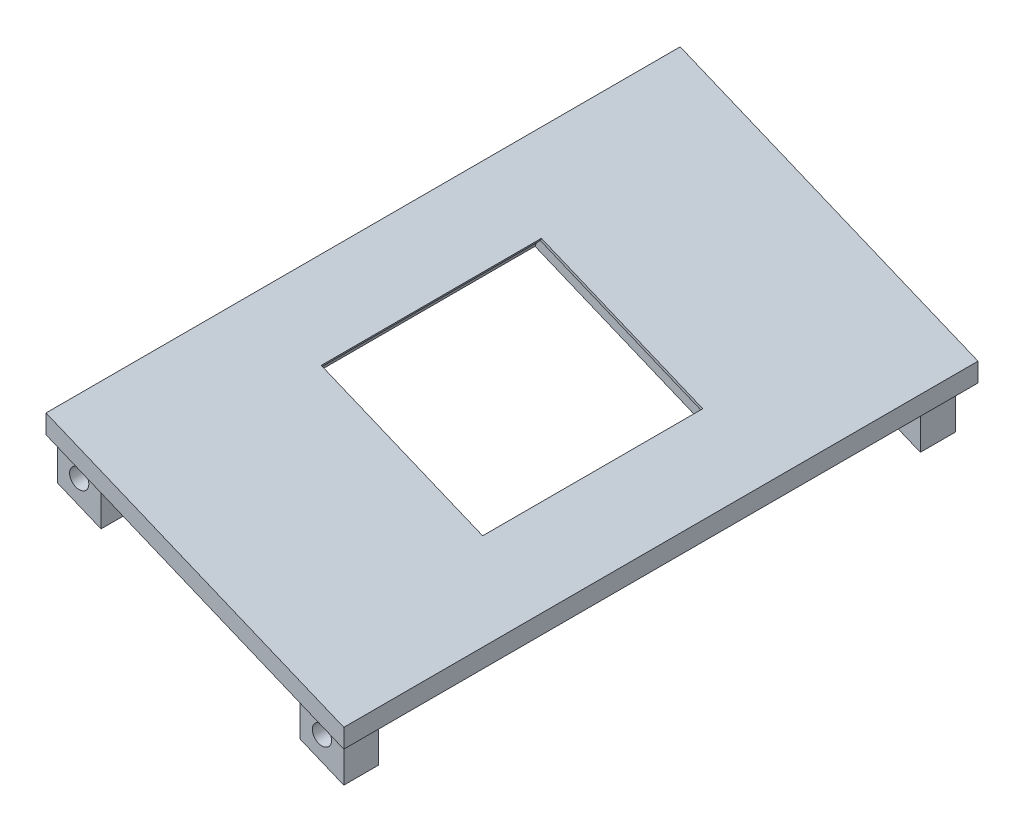
SolidWorks part; units mm, degrees
ref_plane "Ebene vorne" through (0, 0, 0) normal (0, 0, 1) x (1, 0, 0)
ref_plane "Ebene oben" through (0, 0, 0) normal (0, 1, 0) x (1, 0, 0)
ref_plane "Ebene rechts" through (0, 0, 0) normal (1, 0, 0) x (0, 0, -1)
sketch "Skizze1" plane through (0, 0, 0) normal (0, 0, 1) x (1, 0, 0)
  line L0 (0, 0) -> (0, 4.3296)
  line L1 (0, 4.3296) -> (68.1823, -23.9125)
  line L2 (68.1823, -23.9125) -> (68.1823, -28.242)
  line L3 (68.1823, -28.242) -> (0, 0)
  dimension "D1" = 112.5
  dimension "D2" = 4
  dimension "D3" = 73.8
extrude "Aufsatz-Linear austragen1" add sketch "Skizze1" along normal blind 145.2
sketch "Skizze4" plane through (0, 0, 145.2) normal (0, 0, 1) x (1, 0, 0)
  line L0 (0, 0) -> (10, -4.1421)
  line L1 (0, 0) -> (68.1823, -28.242) construction
  line L2 (10, -4.1421) -> (10, -14.9661)
  line L3 (10, -14.9661) -> (0, -10.8239)
  line L4 (0, -10.8239) -> (0, 0)
  line L5 (55.5823, -23.0229) -> (65.5823, -27.1651)
  line L6 (65.5823, -27.1651) -> (65.5823, -37.989)
  line L7 (65.5823, -37.989) -> (55.5823, -33.8469)
  line L8 (55.5823, -33.8469) -> (55.5823, -23.0229)
  line L9 (68.1823, -28.242) -> (68.1823, -23.9125) construction
  dimension "D1" = 10
  dimension "D2" = 10
  dimension "D3" = 2.6
extrude "Aufsatz-Linear austragen2" add sketch "Skizze4" against normal up to surface (145.2 mm away) up to face at (34.0912, -11.9562, 0)
sketch "Skizze5" plane through (0, 0, 145.2) normal (0, 0, 1) x (1, 0, 0)
  line L0 (0, -10.8239) -> (10, -4.1421) construction
  line L1 (55.5823, -33.8469) -> (65.5823, -27.1651) construction
  line L2 (55.5823, -33.8469) -> (65.5823, -37.989) construction
  line L3 (55.5823, -23.0229) -> (55.5823, -33.8469) construction
  line L4 (55.5823, -23.0229) -> (65.5823, -37.989) construction
  line L5 (10, -14.9661) -> (0, 0) construction
  circle A0 centre (5, -7.483) radius 2.2
  circle A1 centre (60.5823, -30.506) radius 2.2
  dimension "D1" = 4.4
extrude "Schnitt-Linear austragen1" cut sketch "Skizze5" against normal through all
sketch "Skizze6" plane through (-3.8268, -9.2388, 0) normal (-0.3827, -0.9239, 0) x (0.9239, -0.3827, 0)
  line L1 (-1.6569, 134.6) -> (75.1279, 134.6)
  line L2 (-1.6569, 134.6) -> (-1.6569, 10.6)
  line L3 (-1.6569, 10.6) -> (75.1279, 10.6)
  line L4 (75.1279, 134.6) -> (75.1279, 10.6)
  line L5 (-1.6569, 134.6) -> (75.1279, 10.6) construction
  line L6 (-1.6569, 10.6) -> (75.1279, 134.6) construction
  line L7 (75.1279, 0) -> (75.1279, 145.2) construction
  line L8 (64.304, 0) -> (75.1279, 0) construction
  line L9 (10.8239, 145.2) -> (60.1619, 145.2) construction
  line L10 (-1.6569, 145.2) -> (-1.6569, 0) construction
  line L12 (75.1279, 145.2) -> (-1.6569, 145.2)
  line L13 (75.1279, 145.2) -> (75.1279, 142.6)
  line L14 (75.1279, 142.6) -> (-1.6569, 142.6)
  line L15 (-1.6569, 145.2) -> (-1.6569, 142.6)
  line L16 (75.1279, 145.2) -> (-1.6569, 142.6) construction
  line L17 (75.1279, 142.6) -> (-1.6569, 145.2) construction
  line L18 (-1.6569, 2.6) -> (75.1279, 2.6)
  line L19 (-1.6569, 2.6) -> (-1.6569, 0)
  line L20 (-1.6569, 0) -> (75.1279, 0)
  line L21 (75.1279, 2.6) -> (75.1279, 0)
  line L22 (-1.6569, 2.6) -> (75.1279, 0) construction
  line L23 (-1.6569, 0) -> (75.1279, 2.6) construction
  point P4 (36.7355, 72.6)
  point P17 (36.7355, 143.9)
  point P23 (36.7355, 1.3)
  dimension "D1" = 10.6
  dimension "D2" = 10.6
  dimension "D3" = 2.6
  dimension "D4" = 2.6
extrude "Schnitt-Linear austragen2" cut sketch "Skizze6" against normal up to surface (10 mm away) up to face at (32.7912, -13.5825, 72.6)
sketch "Skizze7" plane through (1.5307, 3.6955, 0) normal (0.3827, 0.9239, 0) x (0.9239, -0.3827, 0)
  line L0 (-1.6569, 0) -> (72.1431, -145.2) construction
  line L1 (15.2431, -47.4) -> (55.2431, -47.4)
  line L2 (15.2431, -47.4) -> (15.2431, -97.8)
  line L3 (15.2431, -97.8) -> (55.2431, -97.8)
  line L4 (55.2431, -47.4) -> (55.2431, -97.8)
  line L5 (15.2431, -47.4) -> (55.2431, -97.8) construction
  line L6 (15.2431, -97.8) -> (55.2431, -47.4) construction
  line L7 (72.1431, -145.2) -> (72.1431, 0) construction
  line L8 (-1.6569, -145.2) -> (72.1431, 0) construction
  line L9 (72.1431, 0) -> (-1.6569, 0) construction
  point P4 (35.2431, -72.6)
  point P13 (72.1431, -0.0936)
  point P17 (35.2431, -72.6)
  dimension "D1" = 40
  dimension "D2" = 50.4
extrude "Schnitt-Linear austragen3" cut sketch "Skizze7" against normal through all
sketch "Skizze8" plane through (0, 0, 0) normal (-0.3827, -0.9239, 0) x (0.9239, -0.3827, 0)
  line L0 (15.2431, 47.4) -> (15.2431, 97.8) construction
  line L1 (14.2431, 46.4) -> (56.2431, 46.4)
  line L2 (14.2431, 46.4) -> (14.2431, 103.8)
  line L3 (14.2431, 103.8) -> (56.2431, 103.8)
  line L4 (56.2431, 46.4) -> (56.2431, 103.8)
  line L5 (14.2431, 46.4) -> (56.2431, 103.8) construction
  line L6 (14.2431, 103.8) -> (56.2431, 46.4) construction
  line L7 (55.2431, 47.4) -> (15.2431, 47.4) construction
  line L8 (55.2431, 97.8) -> (55.2431, 47.4) construction
  line L9 (15.2431, 97.8) -> (55.2431, 97.8) construction
  point P4 (35.2431, 75.1)
  point P9 (57.1985, 46.4)
  dimension "D1" = 1
  dimension "D2" = 1
  dimension "D3" = 1
  dimension "D4" = 6
extrude "Schnitt-Linear austragen4" cut sketch "Skizze8" against normal blind 3.4
equation "\"D2@Skizze8\"=\"D1@Skizze8\""
equation "\"D3@Skizze8\"=\"D1@Skizze8\""
